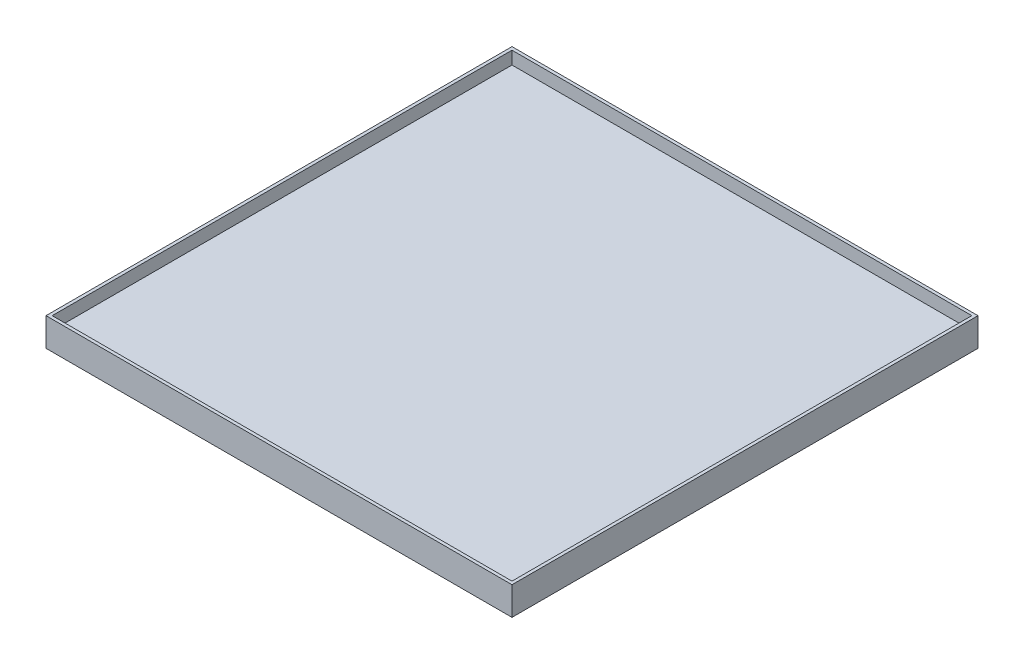
SolidWorks part; units mm, degrees
ref_plane "Plan de face" through (0, 0, 0) normal (0, 0, 1) x (1, 0, 0)
ref_plane "Plan de dessus" through (0, 0, 0) normal (0, 1, 0) x (1, 0, 0)
ref_plane "Plan de droite" through (0, 0, 0) normal (1, 0, 0) x (0, 0, -1)
sketch "Esquisse1" plane through (0, 0, 0) normal (0, 1, 0) x (1, 0, 0)
  line L1 (-905, 905) -> (905, 905)
  line L2 (-905, 905) -> (-905, -905)
  line L3 (-905, -905) -> (905, -905)
  line L4 (905, 905) -> (905, -905)
  dimension "D1" = 1810
  dimension "D2" = 1810
  dimension "D3" = 905
  dimension "D4" = 905
extrude "Boss.-Extru.1" add sketch "Esquisse1" along normal blind 10
sketch "Esquisse2" plane through (0, 0, 0) normal (0, -1, 0) x (-1, 0, 0)
  line L0 (875, -875) -> (875, 875)
  line L1 (905, -905) -> (-905, -905)
  line L2 (905, -905) -> (905, 905)
  line L3 (905, 905) -> (-905, 905)
  line L4 (-905, -905) -> (-905, 905)
  line L5 (875, 875) -> (-875, 875)
  line L6 (-875, -875) -> (-875, 875)
  line L7 (875, -875) -> (-875, -875)
  dimension "D1" = 30
extrude "Boss.-Extru.2" add sketch "Esquisse2" along normal blind 50
sketch "Esquisse3" plane through (0, 0, 0) normal (0, -1, 0) x (-1, 0, 0)
  line L0 (875, -875) -> (875, 875) construction
  line L1 (875, -305) -> (-875, -305)
  line L2 (875, -305) -> (875, -275)
  line L3 (875, -275) -> (-875, -275)
  line L4 (-875, -305) -> (-875, -275)
  line L5 (-875, 875) -> (-875, -875) construction
  line L6 (875, -875) -> (875, 875) construction
  line L7 (875, 275) -> (-875, 275)
  line L8 (875, 275) -> (875, 305)
  line L9 (875, 305) -> (-875, 305)
  line L10 (-875, 275) -> (-875, 305)
  line L11 (-905, -905) -> (905, -905) construction
  line L12 (905, 905) -> (-905, 905) construction
  dimension "D1" = 30
  dimension "D2" = 30
  dimension "D3" = 600
  dimension "D4" = 600
extrude "Boss.-Extru.3" add sketch "Esquisse3" along normal blind 50
sketch "Esquisse4" plane through (0, 0, 0) normal (0, -1, 0) x (-1, 0, 0)
  line L0 (-875, -875) -> (875, -875) construction
  line L1 (335, -875) -> (305, -875)
  line L2 (335, -875) -> (335, 875)
  line L3 (335, 875) -> (305, 875)
  line L4 (305, -875) -> (305, 875)
  line L5 (875, 875) -> (-875, 875) construction
  line L6 (-875, -875) -> (875, -875) construction
  line L7 (-305, -875) -> (-335, -875)
  line L8 (-305, -875) -> (-305, 875)
  line L9 (-305, 875) -> (-335, 875)
  line L10 (-335, -875) -> (-335, 875)
  line L11 (905, -905) -> (905, 905) construction
  line L12 (-905, 905) -> (-905, -905) construction
  dimension "D1" = 30
  dimension "D2" = 30
  dimension "D3" = 600
  dimension "D4" = 600
extrude "Boss.-Extru.4" add sketch "Esquisse4" along normal blind 50
sketch "Esquisse5" plane through (0, 10, 0) normal (0, 1, 0) x (1, 0, 0)
  line L0 (-893, 893) -> (-893, -893)
  line L1 (-905, 905) -> (905, 905)
  line L2 (-905, 905) -> (-905, -905)
  line L3 (-905, -905) -> (905, -905)
  line L4 (905, 905) -> (905, -905)
  line L5 (-893, -893) -> (893, -893)
  line L6 (893, 893) -> (893, -893)
  line L7 (-893, 893) -> (893, 893)
  dimension "D1" = 12
extrude "Boss.-Extru.5" add sketch "Esquisse5" along normal blind 50
